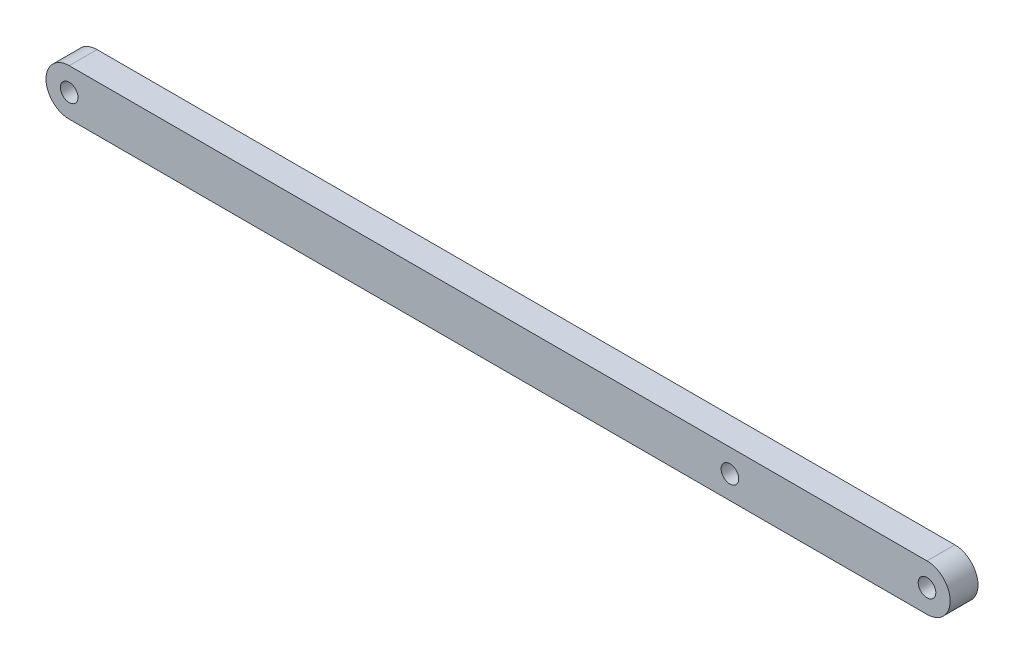
SolidWorks part; units mm, degrees
material "MDF"
ref_plane "Front Plane" through (0, 0, 0) normal (0, 0, 1) x (1, 0, 0)
ref_plane "Top Plane" through (0, 0, 0) normal (0, 1, 0) x (1, 0, 0)
ref_plane "Right Plane" through (0, 0, 0) normal (1, 0, 0) x (0, 0, -1)
sketch "Sketch1" plane through (0, 0, 0) normal (0, 0, 1) x (1, 0, 0)
  line L0 (0, -5) -> (0, 5) construction
  line L1 (-92.5, 5) -> (92.5, 5)
  line L2 (-92.5, -5) -> (92.5, -5)
  line L3 (92.5, 0) -> (-92.5, 0) construction
  line L4 (0, 0) -> (50, 0) construction
  arc A0 (92.5, 5) -> (92.5, -5) centre (92.5, 0) cw
  arc A1 (-92.5, 5) -> (-92.5, -5) centre (-92.5, 0) ccw
  circle A2 centre (-92.5, 0) radius 1.9
  circle A3 centre (92.5, 0) radius 1.9
  circle A4 centre (50, 0) radius 1.9
  point P4 (0, 0)
  point P8 (0, 5)
  point P11 (0, -5)
  point P13 (0, 0)
  dimension "D3" = 3.8
  dimension "D4" = 3.8
  dimension "D5" = 3.8
  dimension "D1" = 10
  dimension "D2" = 185
  dimension "D6" = 50
extrude "Boss-Extrude1" add sketch "Sketch1" along normal blind 6
sketch "Sketch2" plane through (0, 0, 6) normal (0, 0, 1) x (1, 0, 0)
  line L0 (92.5, 5) -> (-92.5, 5) construction
  line L1 (-92.5, 1.9) -> (-92.5, -1.9) construction
  line L2 (-87.5, -2.5) -> (45, -2.5)
  line L3 (-87.5, -2.5) -> (-87.5, 2.5)
  line L4 (-87.5, 2.5) -> (45, 2.5)
  line L5 (45, -2.5) -> (45, 2.5)
  line L6 (-87.5, -2.5) -> (45, 2.5) construction
  line L7 (-87.5, 2.5) -> (45, -2.5) construction
  line L8 (55, -2.5) -> (87.5, -2.5)
  line L9 (55, -2.5) -> (55, 2.5)
  line L10 (55, 2.5) -> (87.5, 2.5)
  line L11 (87.5, -2.5) -> (87.5, 2.5)
  line L12 (55, -2.5) -> (87.5, 2.5) construction
  line L13 (55, 2.5) -> (87.5, -2.5) construction
  line L14 (92.5, 1.9) -> (92.5, -1.9) construction
  line L15 (50, 1.9) -> (50, -1.9) construction
  circle A0 centre (-92.5, 0) radius 1.9 construction
  circle A1 centre (92.5, 0) radius 1.9 construction
  circle A2 centre (50, 0) radius 1.9 construction
  point P4 (0, 0)
  dimension "D1" = 5
  dimension "D2" = 5
  dimension "D3" = 5
  dimension "D4" = 5
  dimension "D5" = 5
  dimension "D6" = 5
  dimension "D7" = 2.5
  dimension "D8" = 2.5
extrude "Cut-Extrude1" [suppressed] cut sketch "Sketch2" against normal through all
sketch "Sketch3" [suppressed] plane through (0, 0, 6) normal (0, 0, 1) x (1, 0, 0)
  line L0 (55, 2.5) -> (-87.5, 2.5) construction
  line L1 (-18.75, 2.5) -> (-8.75, 2.5)
  line L2 (-18.75, 2.5) -> (-18.75, -2.5)
  line L3 (-18.75, -2.5) -> (-8.75, -2.5)
  line L4 (-8.75, 2.5) -> (-8.75, -2.5)
  line L5 (-18.75, 2.5) -> (-8.75, -2.5) construction
  line L6 (-18.75, -2.5) -> (-8.75, 2.5) construction
  line L7 (-87.5, -2.5) -> (55, -2.5) construction
  line L8 (-87.5, 2.5) -> (-87.5, -2.5) construction
  point P4 (-13.75, 0)
  dimension "D1" = 68.75
  dimension "D2" = 10
extrude "Boss-Extrude2" [suppressed] add sketch "Sketch3" against normal through all
